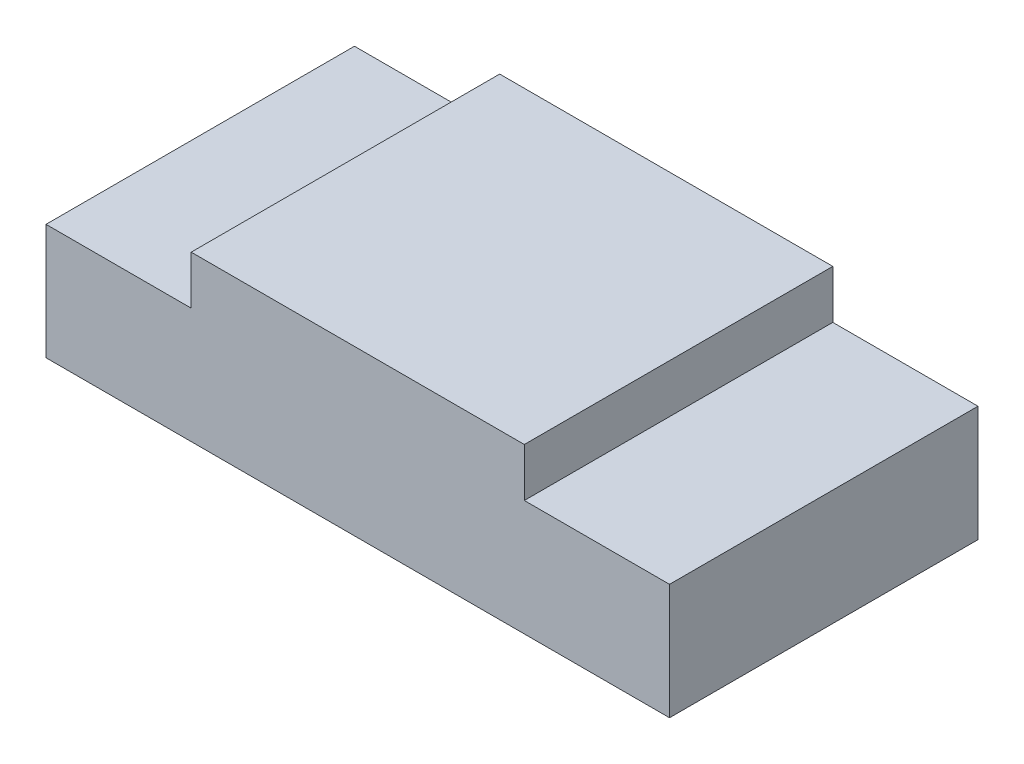
SolidWorks part; units mm, degrees
ref_plane "Front Plane" through (0, 0, 0) normal (0, 0, 1) x (1, 0, 0)
ref_plane "Top Plane" through (0, 0, 0) normal (0, 1, 0) x (1, 0, 0)
ref_plane "Right Plane" through (0, 0, 0) normal (1, 0, 0) x (0, 0, -1)
sketch "Sketch1" plane through (0, 0, 0) normal (0, 1, 0) x (1, 0, 0)
  line L1 (-38.8158, 28.4925) -> (1167.6842, 28.4925)
  line L2 (-38.8158, 28.4925) -> (-38.8158, -568.4075)
  line L3 (-38.8158, -568.4075) -> (1167.6842, -568.4075)
  line L4 (1167.6842, 28.4925) -> (1167.6842, -568.4075)
  dimension "D1" = 1206.5
  dimension "D2" = 596.9
extrude "Extrude1" add sketch "Sketch1" along normal blind 317.5
sketch "Sketch2" plane through (0, 0, 568.4075) normal (0, 0, 1) x (1, 0, 0)
  line L0 (564.4342, 317.5) -> (564.4342, 0) construction
  line L1 (1167.6842, 317.5) -> (886.7263, 317.5)
  line L2 (1167.6842, 317.5) -> (1167.6842, 223.641)
  line L3 (1167.6842, 223.641) -> (886.7263, 223.641)
  line L4 (886.7263, 317.5) -> (886.7263, 223.641)
  line L5 (-38.8158, 317.5) -> (1167.6842, 317.5) construction
  line L6 (-38.8158, 0) -> (1167.6842, 0) construction
  line L7 (242.142, 317.5) -> (242.142, 223.641)
  line L8 (-38.8158, 223.641) -> (242.142, 223.641)
  line L9 (-38.8158, 317.5) -> (-38.8158, 223.641)
  line L10 (-38.8158, 317.5) -> (242.142, 317.5)
extrude "Extrude2" cut sketch "Sketch2" against normal through all
